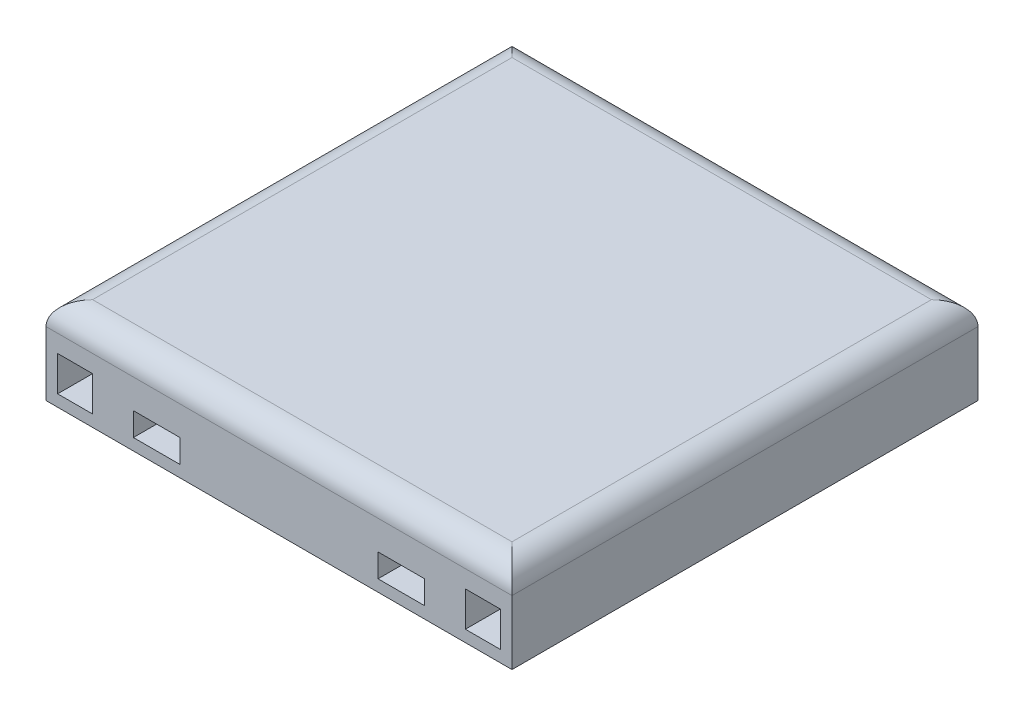
SolidWorks part; units mm, degrees
ref_plane "前视基准面" through (0, 0, 0) normal (0, 0, 1) x (1, 0, 0)
ref_plane "上视基准面" through (0, 0, 0) normal (0, 1, 0) x (1, 0, 0)
ref_plane "右视基准面" through (0, 0, 0) normal (1, 0, 0) x (0, 0, -1)
sketch "草图1" plane through (0, 0, 0) normal (0, 1, 0) x (1, 0, 0)
  line L1 (-40, -40) -> (40, -40)
  line L2 (-40, -40) -> (-40, 40)
  line L3 (-40, 40) -> (40, 40)
  line L4 (40, -40) -> (40, 40)
  line L5 (-40, -40) -> (40, 40) construction
  line L6 (-40, 40) -> (40, -40) construction
  point P0 (0, 0)
  dimension "D1" = 80
  dimension "D2" = 80
extrude "凸台-拉伸1" add sketch "草图1" along normal mid plane 15
fillet "圆角1" radius 4 4 edges at (0, 7.5, 40) (-40, 7.5, 0) (0, 7.5, -40) (40, 7.5, 0)
sketch "草图2" plane through (0, 0, 40) normal (0, 0, 1) x (1, 0, 0)
  line L0 (-40, 3.5) -> (-40, -7.5) construction
  line L1 (-38, 0.5) -> (-32, 0.5)
  line L2 (-38, 0.5) -> (-38, -5.5)
  line L3 (-38, -5.5) -> (-32, -5.5)
  line L4 (-32, 0.5) -> (-32, -5.5)
  line L5 (-25, -1.5) -> (-17, -1.5)
  line L6 (-25, -1.5) -> (-25, -5.5)
  line L7 (-25, -5.5) -> (-17, -5.5)
  line L8 (-17, -1.5) -> (-17, -5.5)
  line L9 (-40, -7.5) -> (40, -7.5) construction
  line L11 (0, 0) -> (0, -7.5) construction
  line L12 (17, -1.5) -> (17, -5.5)
  line L13 (25, -5.5) -> (17, -5.5)
  line L14 (25, -1.5) -> (25, -5.5)
  line L15 (25, -1.5) -> (17, -1.5)
  line L16 (32, 0.5) -> (32, -5.5)
  line L17 (38, -5.5) -> (32, -5.5)
  line L18 (38, 0.5) -> (38, -5.5)
  line L19 (38, 0.5) -> (32, 0.5)
  dimension "D1" = 6
  dimension "D2" = 6
  dimension "D3" = 4
  dimension "D4" = 8
  dimension "D5" = 2
  dimension "D6" = 2
  dimension "D7" = 7
extrude "切除-拉伸1" cut sketch "草图2" against normal blind 8
